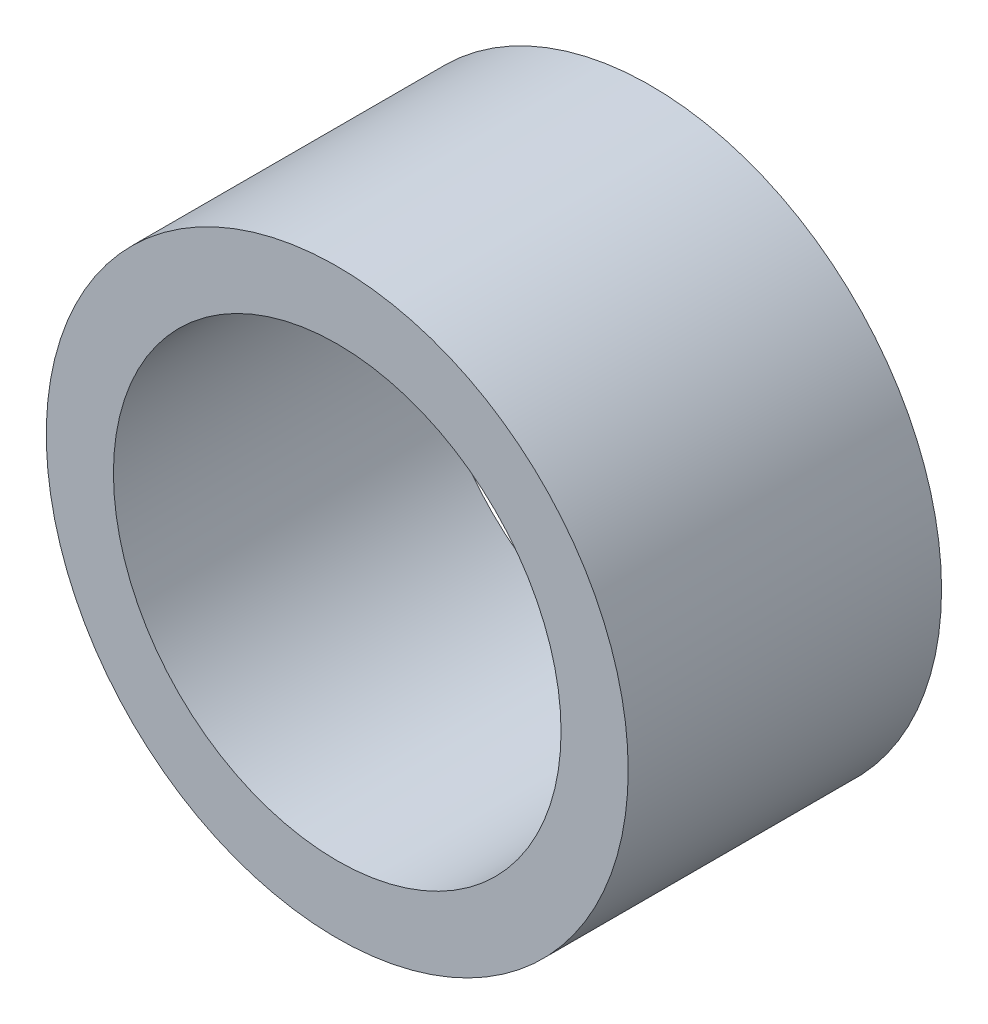
SolidWorks part; units mm, degrees
ref_plane "前视基准面" through (0, 0, 0) normal (0, 0, 1) x (1, 0, 0)
ref_plane "上视基准面" through (0, 0, 0) normal (0, 1, 0) x (1, 0, 0)
ref_plane "右视基准面" through (0, 0, 0) normal (1, 0, 0) x (0, 0, -1)
sketch "草图1" plane through (0, 0, 0) normal (0, 0, 1) x (1, 0, 0)
  circle A0 centre (0, 0) radius 5
  circle A1 centre (0, 0) radius 6.5
  dimension "D1" = 13
  dimension "D2" = 10
extrude "凸台-拉伸1" add sketch "草图1" along normal blind 7
